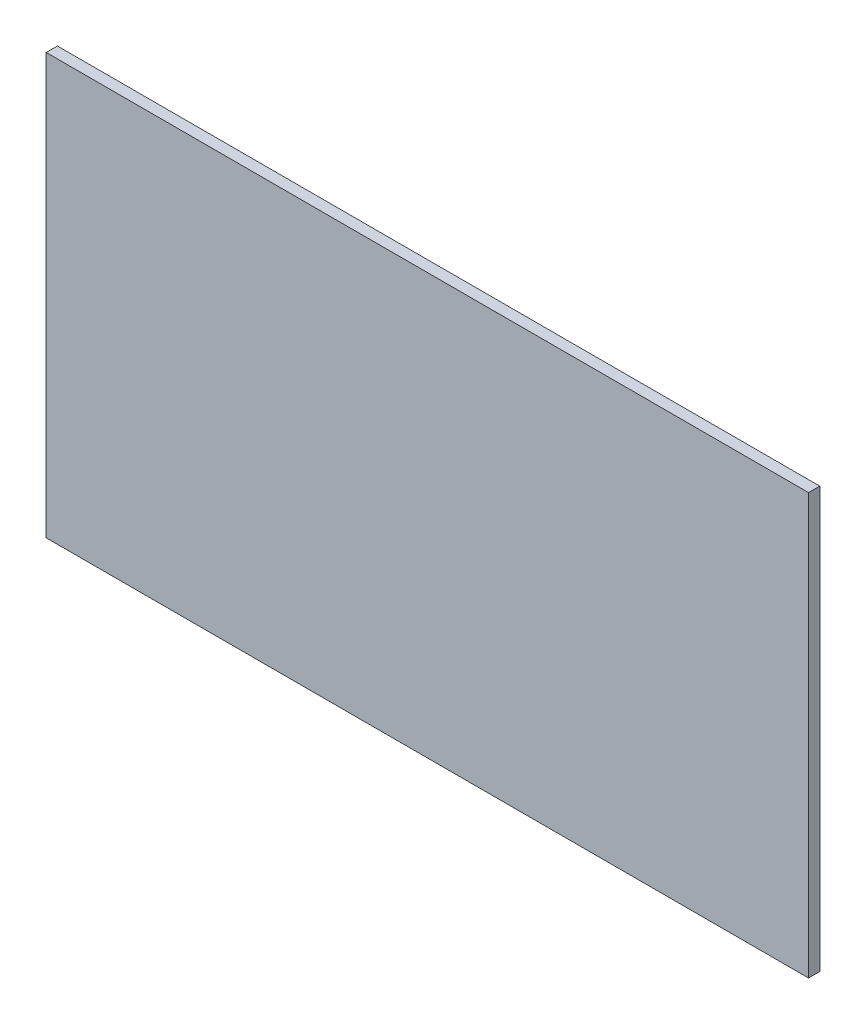
SolidWorks part; units mm, degrees
ref_plane "前视基准面" through (0, 0, 0) normal (0, 0, 1) x (1, 0, 0)
ref_plane "上视基准面" through (0, 0, 0) normal (0, 1, 0) x (1, 0, 0)
ref_plane "右视基准面" through (0, 0, 0) normal (1, 0, 0) x (0, 0, -1)
sketch "草图1" plane through (0, 0, 0) normal (0, 0, 1) x (1, 0, 0)
  line L1 (-136, 75) -> (136, 75)
  line L2 (-136, 75) -> (-136, -75)
  line L3 (-136, -75) -> (136, -75)
  line L4 (136, 75) -> (136, -75)
  line L5 (-136, 75) -> (136, -75) construction
  line L6 (-136, -75) -> (136, 75) construction
  point P0 (0, 0)
  dimension "D1" = 272
  dimension "D2" = 150
extrude "凸台-拉伸1" add sketch "草图1" along normal blind 4
